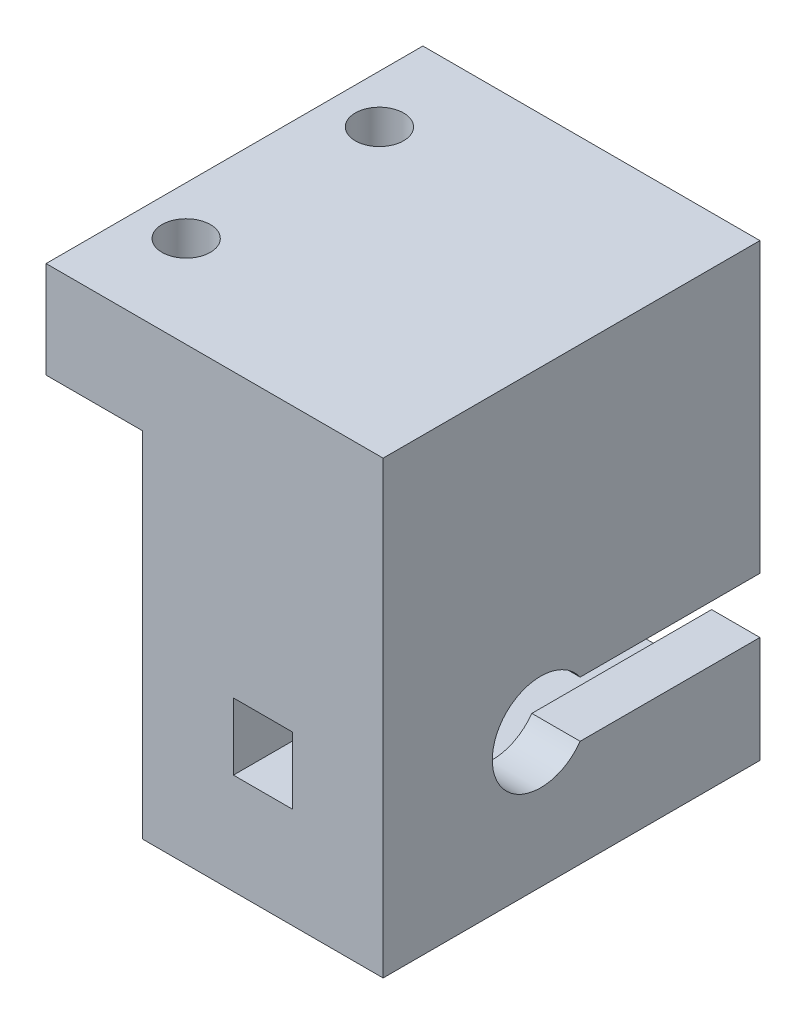
SolidWorks part; units mm, degrees
ref_plane "Front Plane" through (0, 0, 0) normal (0, 0, 1) x (1, 0, 0)
ref_plane "Top Plane" through (0, 0, 0) normal (0, 1, 0) x (1, 0, 0)
ref_plane "Right Plane" through (0, 0, 0) normal (1, 0, 0) x (0, 0, -1)
sketch "Sketch1" plane through (0, 0, 0) normal (0, 0, 1) x (1, 0, 0)
  line L0 (-15.8, 17.65) -> (15.8, 17.65)
  line L1 (-9.45, -11.3) -> (9.45, -11.3)
  line L2 (-9.45, -11.3) -> (-9.45, 11.3)
  line L3 (-9.45, 11.3) -> (9.45, 11.3)
  line L4 (9.45, -11.3) -> (9.45, 11.3)
  line L7 (15.8, -17.65) -> (15.8, 17.65)
  line L8 (-15.8, -17.65) -> (15.8, -17.65)
  line L9 (-15.8, -17.65) -> (-15.8, 17.65)
  point P0 (0, 0)
  dimension "D1" = 22.6
  dimension "D2" = 18.9
  dimension "D3" = 6.35
extrude "Boss-Extrude1" add sketch "Sketch1" along normal blind 40
sketch "Sketch2" plane through (0, 0, 40) normal (0, 0, 1) x (1, 0, 0)
  line L1 (-15.8, 17.65) -> (15.8, 17.65)
  line L2 (-15.8, 17.65) -> (-15.8, -17.65)
  line L3 (-15.8, -17.65) -> (15.8, -17.65)
  line L4 (15.8, 17.65) -> (15.8, -17.65)
  line L9 (-15.8, 17.65) -> (15.8, 17.65)
  line L10 (-15.8, 17.65) -> (-15.8, -17.65)
  line L11 (-15.8, -17.65) -> (15.8, -17.65)
  line L12 (15.8, 17.65) -> (15.8, -17.65)
  point P6 (0, 0)
  line M1 (-15.8, 17.65) -> (-15.8, -17.65)
  line M2 (-15.8, -17.65) -> (15.8, -17.65)
  line M3 (15.8, -17.65) -> (15.8, 17.65)
  line M4 (15.8, 17.65) -> (-15.8, 17.65)
  line M5 (9.45, 11.3) -> (9.45, -11.3)
  line M6 (9.45, -11.3) -> (-9.45, -11.3)
  line M7 (-9.45, -11.3) -> (-9.45, 11.3)
  line M8 (-9.45, 11.3) -> (9.45, 11.3)
extrude "Boss-Extrude2" add sketch "Sketch2" along normal blind 9.525 contours M4 M1 M2 M3 M8 M5 M6 M7 | M5 M8 M7 M6
sketch "Sketch3" plane through (0, 0, 40) normal (0, 0, -1) x (-1, 0, 0)
  line L1 (-3.8745, 4.3943) -> (3.8745, 4.3943)
  line L2 (-3.8745, 4.3943) -> (-3.8745, -4.3943)
  line L3 (-3.8745, -4.3943) -> (3.8745, -4.3943)
  line L4 (3.8745, 4.3943) -> (3.8745, -4.3943)
  line L5 (-3.8745, 4.3943) -> (3.8745, -4.3943) construction
  line L6 (-3.8745, -4.3943) -> (3.8745, 4.3943) construction
  point P0 (0, 0)
extrude "Cut-Extrude1" cut sketch "Sketch3" against normal blind 12.7
sketch "Sketch5" plane through (15.8, 0, 0) normal (1, 0, 0) x (0, 0, -1)
  line L1 (-40.0276, 0) -> (-28.8276, 0) construction
  line L2 (-28.8276, 3.65) -> (0, 3.65)
  line L3 (0, -17.65) -> (0, 17.65) construction
  line L4 (0, 3.65) -> (0, -3.65)
  line L5 (0, -3.65) -> (-28.8276, -3.65)
  arc A0 (-28.8276, 3.65) -> (-28.8276, -3.65) centre (-28.8276, 0) ccw
  dimension "D2" = 7.3
  dimension "D1" = 11.2
extrude "Cut-Extrude2" cut sketch "Sketch5" against normal blind 31.75
sketch "Sketch6" plane through (0, 17.65, 0) normal (0, 1, 0) x (1, 0, 0)
  line L1 (-15.8, 0) -> (15.8, 0)
  line L2 (-15.8, 0) -> (-15.8, -49.525)
  line L3 (-15.8, -49.525) -> (15.8, -49.525)
  line L4 (15.8, 0) -> (15.8, -49.525)
extrude "Boss-Extrude3" add sketch "Sketch6" along normal blind 11.176
sketch "Sketch7" plane through (15.8, 0, 0) normal (1, 0, 0) x (0, 0, -1)
  line L0 (0, 3.65) -> (0, 28.826) construction
  line L1 (-49.525, 28.826) -> (0, 28.826)
  line L2 (-49.525, 28.826) -> (-49.525, 22.476)
  line L3 (-49.525, 22.476) -> (0, 22.476)
  line L4 (0, 28.826) -> (0, 22.476)
  dimension "D1" = 6.35
extrude "Boss-Extrude4" add sketch "Sketch7" along normal blind 12.7 and the other way blind 44.45
sketch "Sketch8" plane through (0, 22.476, 0) normal (0, -1, 0) x (1, 0, 0)
  circle A1 centre (-22.225, 24.7625) radius 3.175
  circle A2 centre (22.15, 37.4346) radius 3.175
  circle A3 centre (22.15, 12.0346) radius 3.175
  dimension "D1" = 25.4
extrude "Cut-Extrude3" cut sketch "Sketch8" against normal blind 6.35
sketch "Sketch9" plane through (0, 22.476, 0) normal (0, -1, 0) x (1, 0, 0)
  line L1 (-15.8, 0) -> (-28.65, 0)
  line L2 (-15.8, 0) -> (-15.8, 49.525)
  line L3 (-15.8, 49.525) -> (-28.65, 49.525)
  line L4 (-28.65, 0) -> (-28.65, 49.525)
extrude "Cut-Extrude4" cut sketch "Sketch9" against normal blind 6.35
sketch "Sketch10" plane through (-15.8, 0, 0) normal (-1, 0, 0) x (0, 0, 1)
  circle A0 centre (28.8276, 0) radius 6.35
ref_plane "Plane1" through (0, 0, 0) normal (1, 0, 0) x (0, 0, -1)
mirror "Mirror1" about plane through (0, 0, 0) normal (1, 0, 0) of "Boss-Extrude4"
sketch "Sketch11" plane through (0, 28.826, 0) normal (0, 1, 0) x (1, 0, 0)
  line L1 (15.8, 0) -> (28.65, 0)
  line L2 (15.8, 0) -> (15.8, -49.525)
  line L3 (15.8, -49.525) -> (28.65, -49.525)
  line L4 (28.65, 0) -> (28.65, -49.525)
  circle A0 centre (-22.15, -37.4625) radius 3.429
  circle A1 centre (-22.15, -12.0625) radius 3.429
  dimension "D2" = 25.4
extrude "Cut-Extrude5" cut sketch "Sketch11" against normal blind 6.35
sketch "Sketch12" plane through (15.8, 0, 0) normal (1, 0, 0) x (0, 0, -1)
  circle A0 centre (-28.8276, 0) radius 6.35
extrude "Cut-Extrude6" cut sketch "Sketch12" against normal blind 6.35
sketch "Sketch13" plane through (0, 28.826, 0) normal (0, 1, 0) x (1, 0, 0)
  line L1 (15.8, -49.525) -> (-28.5, -49.525)
  line L2 (15.8, -49.525) -> (15.8, 0)
  line L3 (15.8, 0) -> (-28.5, 0)
  line L4 (-28.5, -49.525) -> (-28.5, 0)
  line L5 (15.8, -49.525) -> (-28.5, 0) construction
  line L6 (15.8, 0) -> (-28.5, -49.525) construction
  circle A0 centre (-22.15, -12.0625) radius 3.175
  circle A1 centre (-22.15, -37.4625) radius 3.175
  point P0 (-6.35, -24.7625)
extrude "Boss-Extrude5" add sketch "Sketch13" along normal blind 12.7
sketch "Sketch14" plane through (0, 22.476, 0) normal (0, -1, 0) x (1, 0, 0)
  line L1 (-28.5, 49.525) -> (-15.8, 49.525)
  line L2 (-28.5, 49.525) -> (-28.5, 0)
  line L3 (-28.5, 0) -> (-15.8, 0)
  line L4 (-15.8, 49.525) -> (-15.8, 0)
  circle A0 centre (-22.15, 37.4625) radius 3.175
  circle A1 centre (-22.15, 12.0625) radius 3.175
extrude "Cut-Extrude7" cut sketch "Sketch14" against normal blind 6.35
